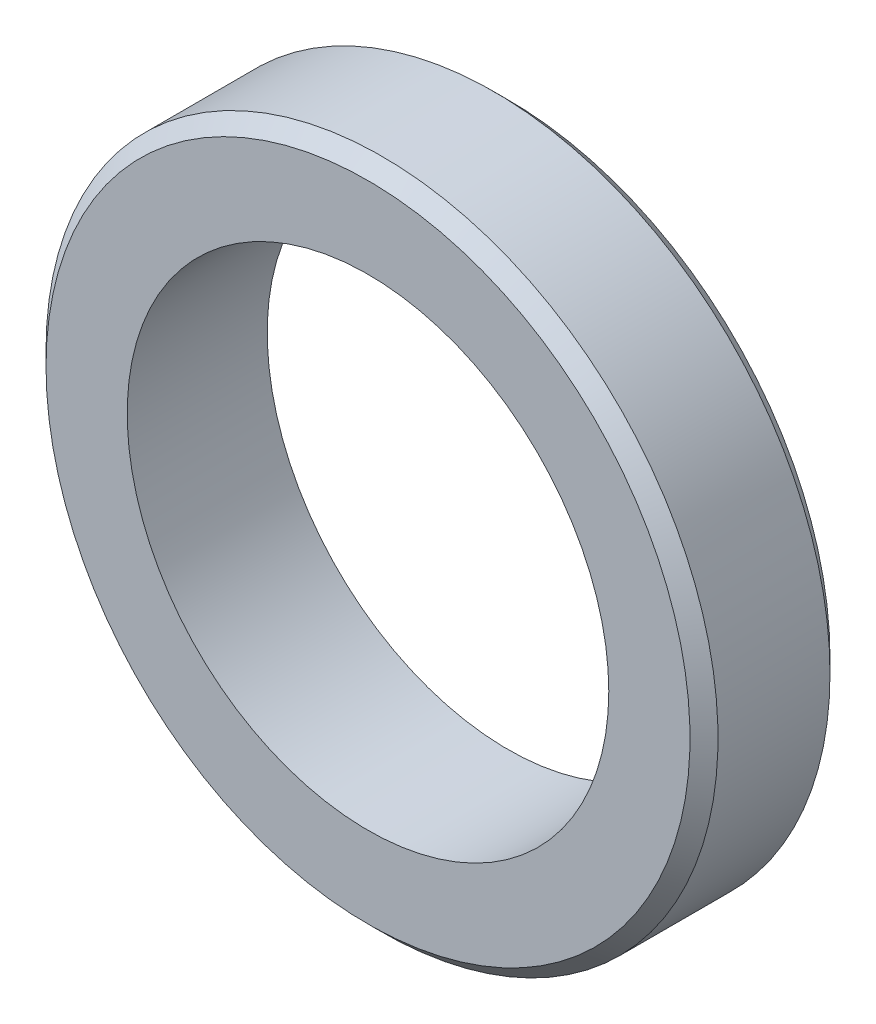
SolidWorks part; units mm, degrees
ref_plane "Piano frontale" through (0, 0, 0) normal (0, 0, 1) x (1, 0, 0)
ref_plane "Piano superiore" through (0, 0, 0) normal (0, 1, 0) x (1, 0, 0)
ref_plane "Piano destro" through (0, 0, 0) normal (1, 0, 0) x (0, 0, -1)
sketch "Schizzo1" plane through (0, 0, 0) normal (0, 0, 1) x (1, 0, 0)
  circle A0 centre (0, 0) radius 12
  dimension "D1" = 24
extrude "Estrusione-Estrusione1" add sketch "Schizzo1" along normal blind 5
sketch "Schizzo3" plane through (0, 0, 5) normal (0, 0, 1) x (1, 0, 0)
  circle A0 centre (0, 0) radius 8.6
  circle A1 centre (0, 0) radius 12 construction
  dimension "D1" = 17.2
extrude "Taglio-Estrusione1" cut sketch "Schizzo3" against normal through all
chamfer "Smusso1" distance 0.5 angle 45 1 edges at (12, 0, 5)
chamfer "Smusso2" distance 0.5 angle 45 1 edges at (12, 0, 0)
